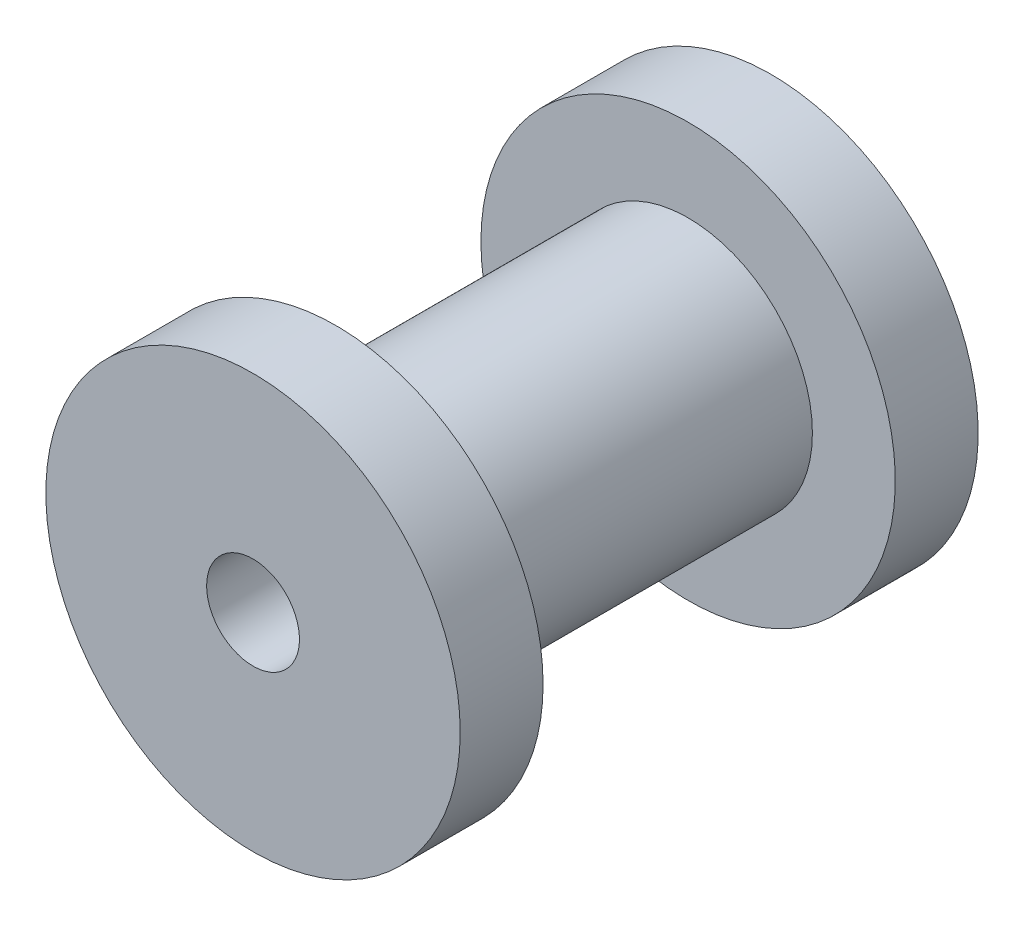
SolidWorks part; units mm, degrees
ref_plane "Front Plane" through (0, 0, 0) normal (0, 0, 1) x (1, 0, 0)
ref_plane "Top Plane" through (0, 0, 0) normal (0, 1, 0) x (1, 0, 0)
ref_plane "Right Plane" through (0, 0, 0) normal (1, 0, 0) x (0, 0, -1)
sketch "Sketch1" plane through (0, 0, 0) normal (0, 0, 1) x (1, 0, 0)
  circle A0 centre (0, 0) radius 9.525
  dimension "D1" = 19.05
extrude "Boss-Extrude1" add sketch "Sketch1" along normal blind 26.9875
sketch "Sketch2" plane through (0, 0, 26.9875) normal (0, 0, 1) x (1, 0, 0)
  circle A0 centre (0, 0) radius 15.875
  dimension "D1" = 31.75
extrude "Boss-Extrude2" add sketch "Sketch2" along normal blind 6.35
sketch "Sketch3" plane through (0, 0, 0) normal (0, 0, -1) x (-1, 0, 0)
  circle A0 centre (0, 0) radius 15.875
  dimension "D1" = 31.75
extrude "Boss-Extrude3" add sketch "Sketch3" along normal blind 6.35
sketch "Sketch4" plane through (0, 0, -6.35) normal (0, 0, -1) x (-1, 0, 0)
  circle A0 centre (0, 0) radius 3.556
  dimension "D1" = 7.112
extrude "Cut-Extrude1" cut sketch "Sketch4" against normal through all
